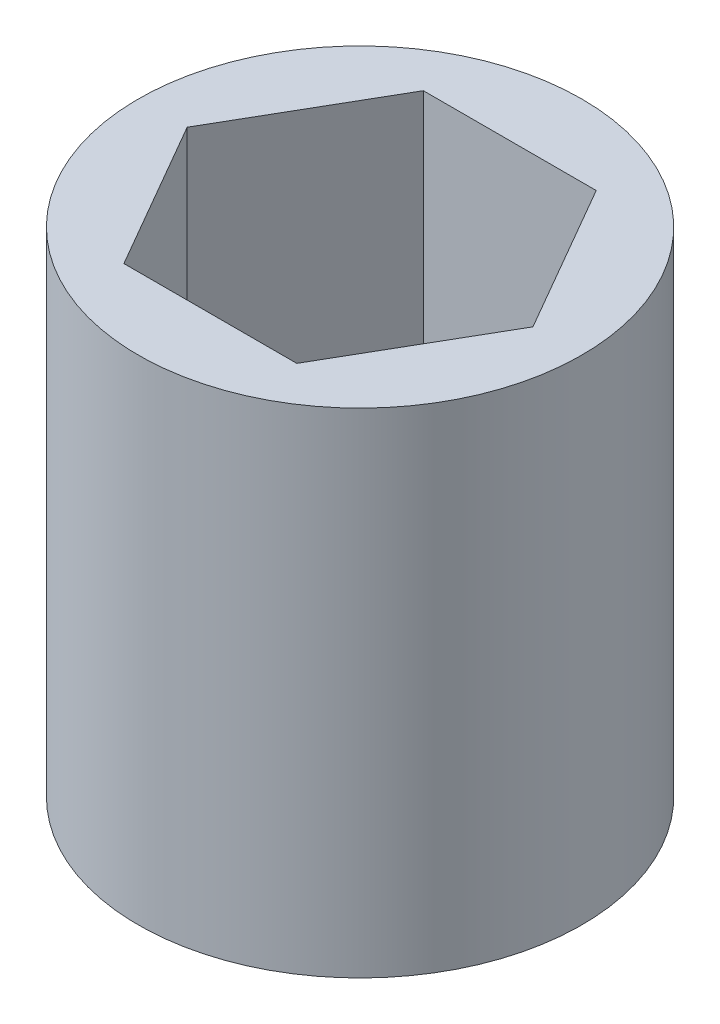
SolidWorks part; units mm, degrees
ref_plane "Front Plane" through (0, 0, 0) normal (0, 0, 1) x (1, 0, 0)
ref_plane "Top Plane" through (0, 0, 0) normal (0, 1, 0) x (1, 0, 0)
ref_plane "Right Plane" through (0, 0, 0) normal (1, 0, 0) x (0, 0, -1)
sketch "Sketch1" plane through (0, 0, 0) normal (0, 1, 0) x (1, 0, 0)
  line L1 (7.9189, 0) -> (3.9595, 6.858)
  line L2 (3.9595, 6.858) -> (-3.9595, 6.858)
  line L3 (-3.9595, 6.858) -> (-7.9189, 0)
  line L4 (-7.9189, 0) -> (-3.9595, -6.858)
  line L5 (-3.9595, -6.858) -> (3.9595, -6.858)
  line L6 (3.9595, -6.858) -> (7.9189, 0)
  circle A0 centre (0, 0) radius 6.858 construction
  circle A1 centre (0, 0) radius 10.16
  dimension "D2" = 20.32
  dimension "D1" = 13.716
extrude "Boss-Extrude1" add sketch "Sketch1" along normal blind 22.606
